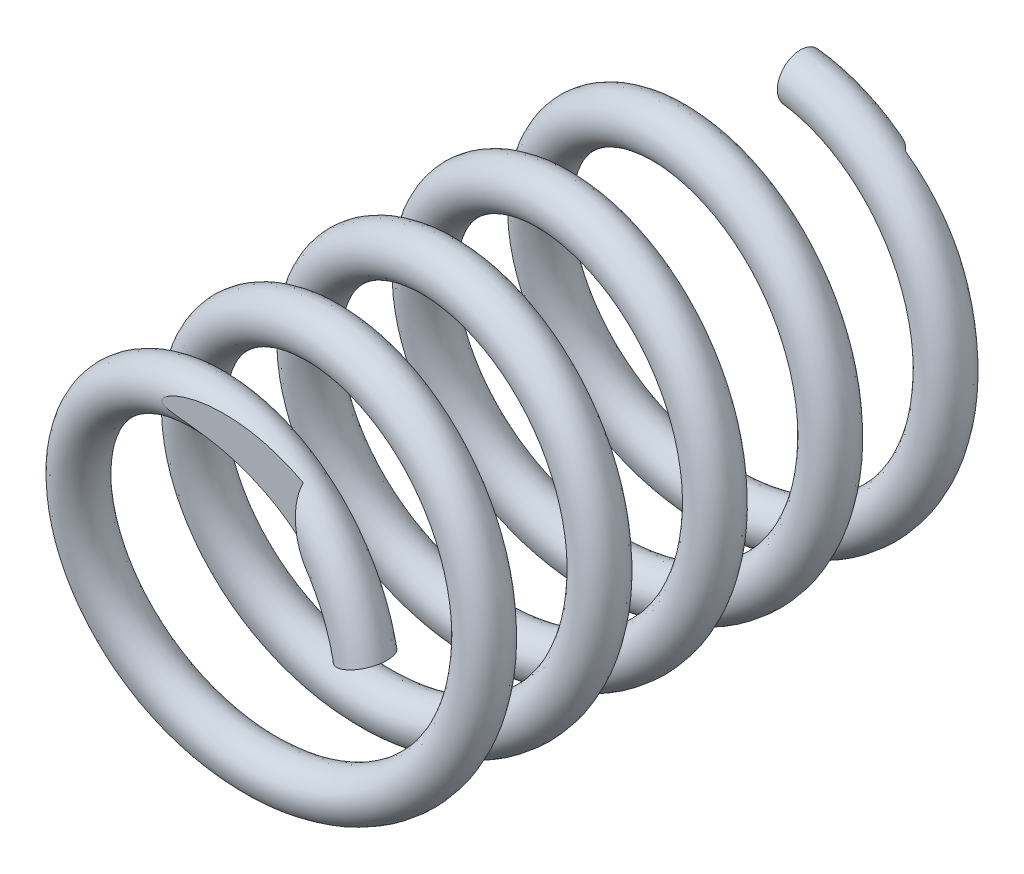
SolidWorks part; units mm, degrees
ref_plane "Front Plane" through (0, 0, 0) normal (0, 0, 1) x (1, 0, 0)
ref_plane "Top Plane" through (0, 0, 0) normal (0, 1, 0) x (1, 0, 0)
ref_plane "Right Plane" through (0, 0, 0) normal (1, 0, 0) x (0, 0, -1)
sketch "Sketch1" plane through (0, 0, 0) normal (0, 0, 1) x (1, 0, 0)
  circle A0 centre (15, -6.7109) radius 37.5
  dimension "D1" = 75
curve "Helix/Spiral3" pitch 25 height 130 turns 5.2
ref_plane "Plane1" through (15, 0, 0) normal (1, 0, 0) x (0, 0, -1)
sketch "Sketch4" plane through (15, 0, 0) normal (1, 0, 0) x (0, 0, -1)
  circle A0 centre (0, 30.7891) radius 5
  spline S0 degree 3 poles (0, 30.7891) (-0.3066, 30.7891) (-0.9223, 30.1149) (-1.8439, 27.1351) (-2.766, 22.3461) (-3.6879, 16.0039) (-4.6099, 8.4474) (-5.5319, 0.0807) (-6.4539, -8.6491) (-7.3759, -17.2752) (-8.2979, -25.3367) (-9.2199, -32.4025) (-10.1418, -38.095) (-11.0638, -42.1099) (-11.9858, -44.2325) (-12.9078, -44.3495) (-13.8298, -42.4545) (-14.7518, -38.6488) (-15.6738, -33.1359) (-16.5957, -26.2105) (-17.5177, -18.2428) (-18.4397, -9.6586) (-19.3617, -0.9168) (-20.2837, 7.5152) (-21.2057, 15.1868) (-22.1277, 21.6878) (-23.0496, 26.6708) (-23.9716, 29.8694) (-24.8936, 31.1126) (-25.8156, 30.334) (-26.7376, 27.5752) (-27.6596, 22.9836) (-28.5816, 16.8047) (-29.5035, 9.3688) (-30.4255, 1.0734) (-31.3475, -7.6382) (-32.2695, -16.3002) (-33.1915, -24.4496) (-34.1135, -31.6507) (-35.0355, -37.5188) (-35.9574, -41.74) (-36.8794, -44.0888) (-37.8014, -44.4395) (-38.7234, -42.7735) (-39.6454, -39.1798) (-40.5674, -33.8505) (-41.4894, -27.0704) (-42.4113, -19.202) (-43.3333, -10.666) (-44.2553, -1.9185) (-45.1773, 6.5728) (-46.0993, 14.354) (-47.0213, 21.0092) (-47.9433, 26.1827) (-48.8652, 29.5978) (-49.7872, 31.0721) (-50.7092, 30.5267) (-51.6312, 27.9908) (-52.5532, 23.5999) (-53.4752, 17.5887) (-54.3972, 10.2787) (-55.3191, 2.0605) (-56.2411, -6.6266) (-57.1631, -15.3182) (-58.0851, -23.5497) (-59.0071, -30.8811) (-59.9291, -36.9205) (-60.8511, -41.3451) (-61.773, -43.9183) (-62.695, -44.5026) (-63.617, -43.0667) (-64.539, -39.6875) (-65.461, -34.5456) (-66.383, -27.9157) (-67.305, -20.1524) (-68.227, -11.6706) (-69.1489, -2.9236) (-70.0709, 5.6209) (-70.9929, 13.5062) (-71.9149, 20.3108) (-72.8369, 25.671) (-73.7589, 29.3002) (-74.6809, 31.0045) (-75.6028, 30.6927) (-76.5248, 28.3815) (-77.4468, 24.1945) (-78.3688, 18.3554) (-79.2908, 11.1764) (-80.2128, 3.0413) (-81.1348, -5.6151) (-82.0567, -14.3301) (-82.9787, -22.6379) (-83.9007, -30.0942) (-84.8227, -36.3007) (-85.7447, -40.9254) (-86.6667, -43.7212) (-87.5887, -44.5386) (-88.5106, -43.334) (-89.4326, -40.1717) (-90.3546, -35.2208) (-91.2766, -28.7459) (-92.1986, -21.0931) (-93.1206, -12.6716) (-94.0426, -3.9314) (-94.9645, 4.6602) (-95.8865, 12.644) (-96.8085, 19.5931) (-97.7305, 25.1362) (-98.6525, 28.9769) (-99.5745, 30.91) (-100.4965, 30.832) (-101.4184, 28.7472) (-102.3404, 24.767) (-103.2624, 19.1042) (-104.1844, 12.0614) (-105.1064, 4.0152) (-106.0284, -4.6044) (-106.9504, -13.3366) (-107.8723, -21.7146) (-108.7943, -29.2906) (-109.7163, -35.6597) (-110.6383, -40.4813) (-111.5603, -43.4977) (-112.4823, -44.5476) (-113.4043, -43.5751) (-114.3262, -40.632) (-115.2482, -35.8757) (-116.1702, -29.5603) (-117.0922, -22.0236) (-118.0142, -13.6684) (-118.9362, -4.9412) (-119.8582, 3.6914) (-120.7801, 11.7679) (-121.7021, 18.8566) (-122.6241, 24.5787) (-123.5461, 28.6281) (-124.4681, 30.7886) (-125.3901, 30.9445) (-126.3121, 29.0875) (-127.234, 25.3172) (-128.1561, 19.8337) (-129.0777, 12.9358) (-129.6934, 7.6259) (-130, 4.8772) knots 0 0 0 0 0.007092 0.014184 0.021277 0.028369 0.035461 0.042553 0.049645 0.056738 0.06383 0.070922 0.078014 0.085106 0.092199 0.099291 0.106383 0.113475 0.120567 0.12766 0.134752 0.141844 0.148936 0.156028 0.163121 0.170213 0.177305 0.184397 0.191489 0.198582 0.205674 0.212766 0.219858 0.22695 0.234043 0.241135 0.248227 0.255319 0.262411 0.269504 0.276596 0.283688 0.29078 0.297872 0.304965 0.312057 0.319149 0.326241 0.333333 0.340426 0.347518 0.35461 0.361702 0.368794 0.375887 0.382979 0.390071 0.397163 0.404255 0.411348 0.41844 0.425532 0.432624 0.439716 0.446809 0.453901 0.460993 0.468085 0.475177 0.48227 0.489362 0.496454 0.503546 0.510638 0.51773 0.524823 0.531915 0.539007 0.546099 0.553191 0.560284 0.567376 0.574468 0.58156 0.588652 0.595745 0.602837 0.609929 0.617021 0.624113 0.631206 0.638298 0.64539 0.652482 0.659574 0.666667 0.673759 0.680851 0.687943 0.695035 0.702128 0.70922 0.716312 0.723404 0.730496 0.737589 0.744681 0.751773 0.758865 0.765957 0.77305 0.780142 0.787234 0.794326 0.801418 0.808511 0.815603 0.822695 0.829787 0.836879 0.843972 0.851064 0.858156 0.865248 0.87234 0.879433 0.886525 0.893617 0.900709 0.907801 0.914894 0.921986 0.929078 0.93617 0.943262 0.950355 0.957447 0.964539 0.971631 0.978723 0.985816 0.992908 1 1 1 1 construction
  dimension "D1" = 10
sweep "Sweep2" add profiles "Sketch4" path "Helix/Spiral3"
sketch "Sketch9" plane through (15, 0, 0) normal (-1, 0, 0) x (0, 0, 1)
  line L1 (-8.9271, 28.4928) -> (0.2911, 28.4928)
  line L2 (-8.9271, 28.4928) -> (-8.9271, -7.6621)
  line L3 (-8.9271, -7.6621) -> (0.2911, -7.6621)
  line L4 (0.2911, 28.4928) -> (0.2911, -7.6621)
extrude "Cut-Extrude1" cut sketch "Sketch9" against normal through all both
sketch "Sketch10" plane through (3.4047, -10.4785, 0) normal (0.309, -0.9511, 0) x (0.9511, 0.309, 0)
  line L1 (43.6589, 138.0885) -> (10.7969, 138.0885)
  line L2 (43.6589, 138.0885) -> (43.6589, 128.9938)
  line L3 (43.6589, 128.9938) -> (10.7969, 128.9938)
  line L4 (10.7969, 138.0885) -> (10.7969, 128.9938)
extrude "Cut-Extrude2" cut sketch "Sketch10" against normal through all both
sketch "Sketch7" plane through (15, 0, 0) normal (1, 0, 0) x (0, 0, -1)
  line L0 (-105.2399, -4.9238) -> (3.5165, -4.9238) construction
